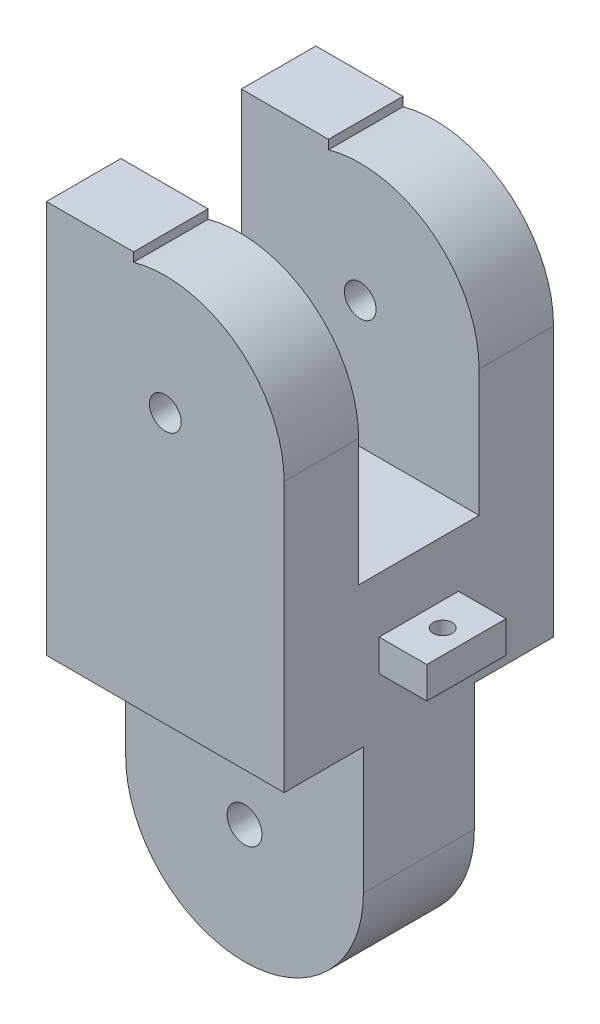
SolidWorks part; units mm, degrees
ref_plane "Front Plane" through (0, 0, 0) normal (0, 0, 1) x (1, 0, 0)
ref_plane "Top Plane" through (0, 0, 0) normal (0, 1, 0) x (1, 0, 0)
ref_plane "Right Plane" through (0, 0, 0) normal (1, 0, 0) x (0, 0, -1)
sketch "Finger_Skeleton" plane through (0, 0, 0) normal (0, 0, -1) x (-1, 0, 0)
  line L0 (0, 0) -> (0, 25)
  line L1 (0, 25) -> (0, 50)
  line L2 (0, 50) -> (0, 73)
  circle A1 centre (0, 0) radius 5 construction
  circle A2 centre (0, 25) radius 5 construction
  circle A3 centre (0, 50) radius 5 construction
  dimension "D4" = 10
  dimension "D5" = 10
  dimension "D6" = 10
  dimension "D1" = 25
  dimension "D2" = 25
  dimension "D3" = 23
sketch "Link1_Outline" plane through (0, 0, 0) normal (0, 0, 1) x (1, 0, 0)
  line L0 (0, 0) -> (0, 25) construction
  line L1 (-7.5, 0) -> (-7.5, 25)
  line L2 (7.5, 0) -> (7.5, 25)
  arc A0 (-7.5, 0) -> (7.5, 0) centre (0, 0) ccw
  arc A1 (7.5, 25) -> (-7.5, 25) centre (0, 25) ccw
  point P4 (0, 12.5)
  dimension "D1" = 15
extrude "Link1_Body" add sketch "Link1_Outline" along normal mid plane 17
sketch "Sketch1" plane through (7.5, 0, 0) normal (1, 0, 0) x (0, 0, -1)
  line L0 (0, 0) -> (0, 25) construction
  line L1 (3.5, -8) -> (9, -8)
  line L2 (3.5, -8) -> (3.5, 7.9981)
  line L3 (3.5, 7.9981) -> (9, 7.9981)
  line L4 (9, -8) -> (9, 7.9981)
  line L5 (-8.5, -7.5) -> (8.5, -7.5) construction
  line L6 (0, 5.5) -> (0, -5.5) construction
  line L7 (-9, -8) -> (-9, 7.9981)
  line L8 (-3.5, 7.9981) -> (-9, 7.9981)
  line L9 (-3.5, -8) -> (-3.5, 7.9981)
  line L10 (-3.5, -8) -> (-9, -8)
  dimension "D1" = 3.5
  dimension "D2" = 5.5
  dimension "D3" = 15.9981
  dimension "D4" = 0.5
extrude "Tongue_Cut" cut sketch "Sketch1" against normal through all both and the other way through all
sketch "Sketch7" plane through (0, 0, 0) normal (0, 0, 1) x (1, 0, 0)
  line L1 (-7.5, 25) -> (-2, 25)
  line L2 (-7.5, 25) -> (-7.5, 32.8)
  line L3 (-7.5, 32.8) -> (-2, 32.8)
  line L4 (-2, 25) -> (-2, 32.8)
  dimension "D1" = 5.5
  dimension "D2" = 7.8
extrude "Boss-Extrude1" add sketch "Sketch7" along normal mid plane 17
sketch "Sketch2" plane through (0, 0, 0) normal (1, 0, 0) x (0, 0, -1)
  line L0 (0, 0) -> (0, 25) construction
  line L1 (3.8, 17) -> (-3.8, 17)
  line L2 (3.8, 17) -> (3.8, 35)
  line L3 (3.8, 35) -> (-3.8, 35)
  line L4 (-3.8, 17) -> (-3.8, 35)
  dimension "D1" = 3.8
  dimension "D2" = 18
  dimension "D3" = 7.6
  dimension "D4" = 17
extrude "Slot_Cut" cut sketch "Sketch2" against normal through all both and the other way through all
sketch "Sketch3" plane through (0, 0, 0) normal (0, 0, 1) x (1, 0, 0)
  circle A0 centre (0, 0) radius 1.1
  circle A1 centre (0, 25) radius 1
  dimension "D1" = 2.2
  dimension "D2" = 2
extrude "Pin_Holes" cut sketch "Sketch3" against normal through all both and the other way through all
sketch "Sketch4" plane through (0, 0, 0) normal (0, 0, 1) x (1, 0, 0)
  line L0 (0, 0) -> (0, 25) construction
  line L1 (7, 13.5) -> (10.5, 13.5)
  line L2 (7, 13.5) -> (7, 11.5)
  line L3 (7, 11.5) -> (10.5, 11.5)
  line L4 (10.5, 13.5) -> (10.5, 11.5)
  dimension "D1" = 7
  dimension "D2" = 3.5
  dimension "D3" = 11.5
  dimension "D4" = 2
extrude "Guide_Block_1" add sketch "Sketch4" along normal mid plane 5
sketch "Sketch5" plane through (0, 0, 0) normal (0, 0, 1) x (1, 0, 0)
  line L0 (0, 0) -> (0, 25) construction
  line L1 (7.0006, 32) -> (10.5006, 32)
  line L2 (7.0006, 32) -> (7.0006, 34)
  line L3 (7.0006, 34) -> (10.5006, 34)
  line L4 (10.5006, 32) -> (10.5006, 34)
  dimension "D1" = 7.0006
  dimension "D2" = 32
  dimension "D3" = 3.5
  dimension "D4" = 2
sketch "Sketch6" plane through (0, 0, 0) normal (0, 1, 0) x (1, 0, 0)
  line L1 (10.5, -2.5) -> (7.5, -2.5) construction
  circle A0 centre (9, 0) radius 0.6
  dimension "D1" = 1.2
  dimension "D2" = 9
  dimension "D3" = 2.5
extrude "Cord_Guides" cut sketch "Sketch6" along normal through all both and the other way through all
